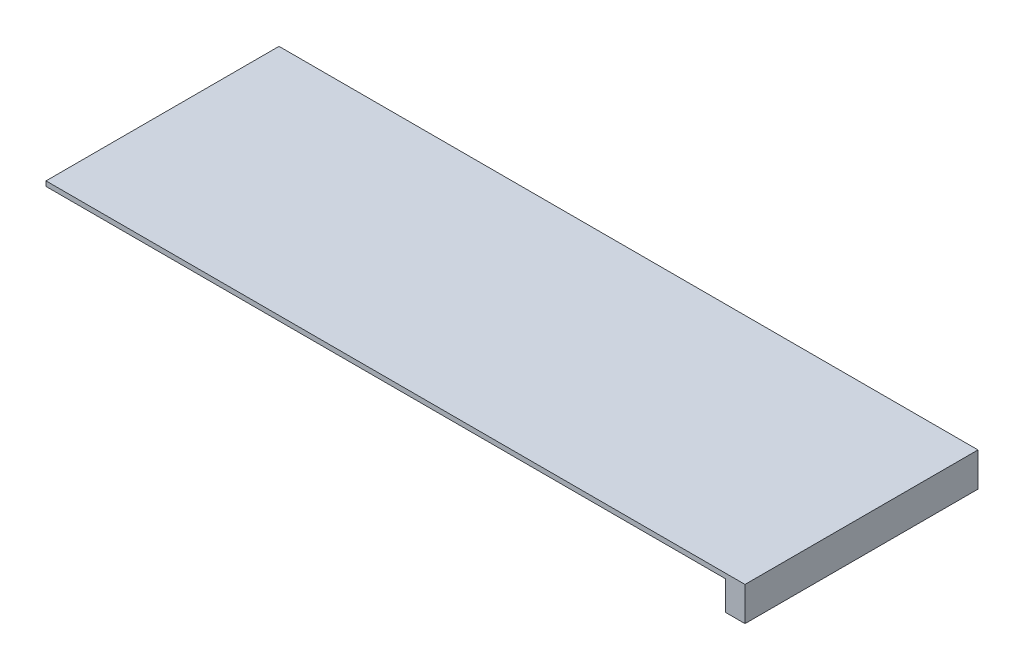
SolidWorks part; units mm, degrees
ref_plane "Front Plane" through (0, 0, 0) normal (0, 0, 1) x (1, 0, 0)
ref_plane "Top Plane" through (0, 0, 0) normal (0, 1, 0) x (1, 0, 0)
ref_plane "Right Plane" through (0, 0, 0) normal (1, 0, 0) x (0, 0, -1)
sketch "Sketch1" plane through (0, 0, 0) normal (0, 1, 0) x (1, 0, 0)
  line L0 (0, 19.05) -> (0, 57.15)
  line L1 (0, 0) -> (57.15, 0)
  line L2 (0, 0) -> (0, 19.05)
  line L3 (0, 19.05) -> (57.15, 19.05)
  line L4 (57.15, 0) -> (57.15, 19.05)
  line L5 (0, 57.15) -> (88.9, 57.15)
  line L6 (88.9, 57.15) -> (57.15, 19.05)
  line L7 (88.9, 57.15) -> (342.9, 57.15)
  line L8 (342.9, 57.15) -> (431.8, -12.7)
  line L9 (342.9, 57.15) -> (88.9, 57.15)
  line L10 (342.9, 57.15) -> (342.9, 38.1)
  line L11 (342.9, 38.1) -> (88.9, 38.1)
  line L12 (88.9, 57.15) -> (88.9, 38.1)
  line L13 (342.9, 57.15) -> (431.8, 57.15)
  line L14 (342.9, 57.15) -> (342.9, -12.7)
  line L15 (342.9, -12.7) -> (431.8, -12.7)
  line L16 (431.8, 57.15) -> (431.8, -12.7)
  line L17 (431.8, -12.7) -> (420.0305, -27.6794)
  line L18 (420.0305, -27.6794) -> (336.3113, 38.1)
  line L19 (57.15, 19.05) -> (73.025, 38.1)
  line L20 (57.15, 19.05) -> (71.1524, 6.1336)
  line L21 (71.1524, 6.1336) -> (103.8794, 45.3805)
  line L22 (57.15, 0) -> (66.0378, 0)
  line L23 (88.9, 57.15) -> (103.8794, 45.3805)
  line L24 (73.025, 38.1) -> (87.6596, 25.9045)
  line L25 (71.1524, 6.1336) -> (64.1512, -2.2625)
extrude "Boss-Extrude1" add sketch "Sketch1" along normal blind 19.05
sketch "Sketch2" plane through (0, 0, 0) normal (0, 0, 1) x (1, 0, 0)
  line L0 (0, 9.525) -> (8.89, 9.525)
  line L1 (0, 19.05) -> (0, 0) construction
  line L2 (0, 9.525) -> (56.515, 9.525)
  circle A0 centre (8.89, 9.525) radius 3.9688
  circle A1 centre (56.515, 9.525) radius 3.9687
extrude "Cut-Extrude1" cut sketch "Sketch2" against normal blind 19.05
sketch "Sketch3" plane through (0, 0, 0) normal (0, -1, 0) x (1, 0, 0)
  line L0 (0, -19.05) -> (0, 0)
  line L1 (0, 0) -> (66.0378, 0)
  line L2 (66.0378, 0) -> (97.8084, -38.1)
  line L3 (97.8084, -38.1) -> (336.3113, -38.1)
  line L4 (336.3113, -38.1) -> (400.9659, 12.7)
  line L5 (400.9659, 12.7) -> (431.8, 12.7)
  line L6 (431.8, 12.7) -> (342.9, -57.15)
  line L7 (342.9, -57.15) -> (88.9, -57.15)
  line L8 (88.9, -57.15) -> (57.15, -19.05)
  line L9 (57.15, -19.05) -> (0, -19.05)
  line L10 (0, -19.05) -> (-12.7, -19.05)
  line L11 (-12.7, -19.05) -> (-12.7, -114.3)
  line L12 (431.8, 12.7) -> (431.8, 38.1)
  line L13 (431.8, 38.1) -> (444.5, 38.1)
  line L15 (-12.7, -114.3) -> (444.5, -114.3)
  line L16 (-12.7, -114.3) -> (-12.7, 38.1)
  line L17 (-12.7, 38.1) -> (444.5, 38.1)
  line L18 (444.5, -114.3) -> (444.5, 38.1)
extrude "Boss-Extrude3" add sketch "Sketch3" along normal blind 19.05 separate body contours L15 L18 L13 L12 L7 L6 L5 L4 L10 L11 | L17 L16 L10 L3 L2 L1 L0 L9 L8 L12
sketch "Sketch4" plane through (0, 0, 0) normal (0, 1, 0) x (1, 0, 0)
  line L1 (444.5, 114.3) -> (-12.7, 114.3)
  line L2 (444.5, 114.3) -> (444.5, -38.1)
  line L3 (444.5, -38.1) -> (-12.7, -38.1)
  line L4 (-12.7, 114.3) -> (-12.7, -38.1)
extrude "Cut-Extrude2" cut sketch "Sketch4" along normal blind 25.4
sketch "Sketch5" plane through (0, -19.05, 0) normal (0, -1, 0) x (1, 0, 0)
  line L0 (0, -19.05) -> (-12.7, -19.05)
  line L1 (-12.7, 38.1) -> (-12.7, -114.3) construction
  line L2 (-12.7, -19.05) -> (57.15, -19.05)
  line L3 (57.15, -19.05) -> (88.9, -57.15)
  line L4 (88.9, -57.15) -> (342.9, -57.15)
  line L5 (342.9, -57.15) -> (431.8, 12.7)
  line L6 (431.8, 12.7) -> (431.8, 38.1)
  line L7 (-12.7, 38.1) -> (444.5, 38.1) construction
  line L8 (431.8, 38.1) -> (-12.7, 38.1)
  line L9 (-12.7, 38.1) -> (-12.7, -19.05)
  line M1 (444.5, 38.1) -> (-12.7, 38.1)
  line M2 (-12.7, 38.1) -> (-12.7, -114.3)
  line M5 (400.9659, 12.7) -> (431.8, 12.7)
  line M10 (0, -19.05) -> (0, 0)
  line M11 (0, 0) -> (66.0378, 0)
  line M12 (66.0378, 0) -> (97.8084, -38.1)
  line M13 (97.8084, -38.1) -> (336.3113, -38.1)
  line M14 (336.3113, -38.1) -> (400.9659, 12.7)
extrude "Cut-Extrude4" cut sketch "Sketch5" against normal blind 25.4 contours L6 L0 M5 M1 M2 M10 M11 M12 M13 M14
sketch "Sketch6" plane through (0, 0, 0) normal (0, 1, 0) x (1, 0, 0)
  line L1 (444.5, -38.1) -> (-12.7, -38.1)
  line L2 (444.5, -38.1) -> (444.5, 114.3)
  line L3 (444.5, 114.3) -> (-12.7, 114.3)
  line L4 (-12.7, -38.1) -> (-12.7, 114.3)
extrude "Boss-Extrude4" add sketch "Sketch6" along normal blind 3.175
